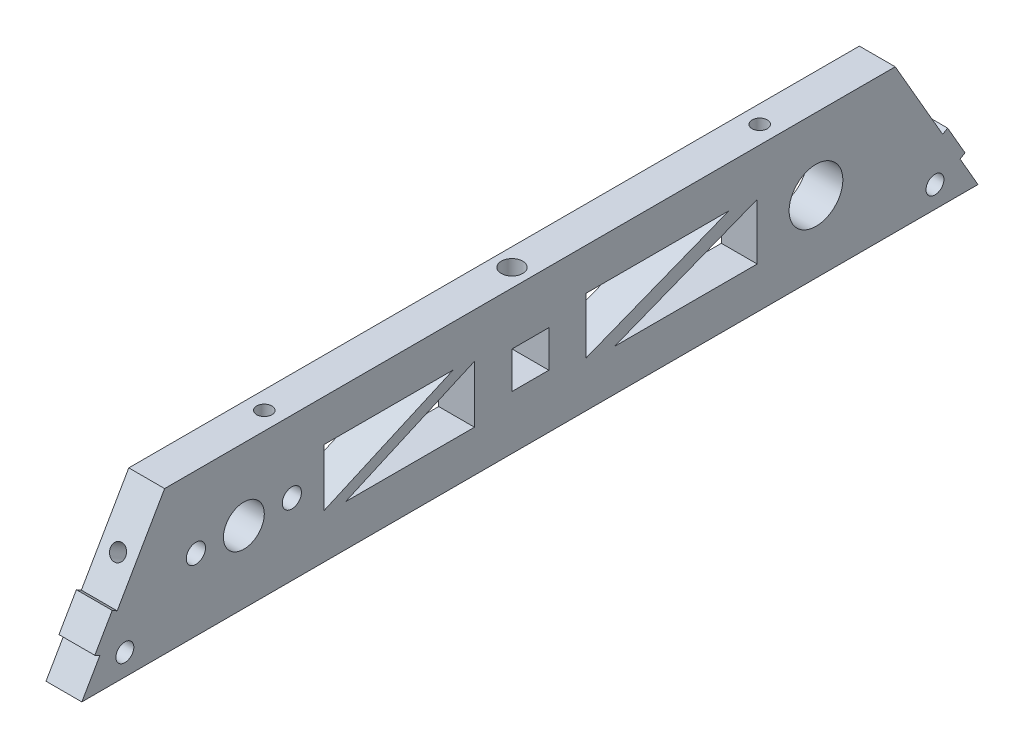
SolidWorks part; units mm, degrees
material "6061-T6 (SS)"
ref_plane "Front Plane" through (0, 0, 0) normal (0, 0, 1) x (1, 0, 0)
ref_plane "Top Plane" through (0, 0, 0) normal (0, 1, 0) x (1, 0, 0)
ref_plane "Right Plane" through (0, 0, 0) normal (1, 0, 0) x (0, 0, -1)
sketch "Sketch1" plane through (0, 0, 0) normal (1, 0, 0) x (0, 0, -1)
  line L0 (0, 0) -> (-14.6647, 25.4)
  line L1 (0, 0) -> (-158.75, 0)
  line L3 (-14.6647, 25.4) -> (-144.0853, 25.4)
  line L4 (-82.55, 9.525) -> (-76.0222, 9.525)
  line L5 (-158.75, 0) -> (-144.0853, 25.4)
  line L6 (-82.55, 9.525) -> (-82.55, 16.0528)
  line L7 (-82.55, 16.0528) -> (-76.0222, 16.0528)
  line L8 (-76.0222, 9.525) -> (-76.0222, 16.0528)
  circle A0 centre (-130.048, 12.7) radius 3.6195
  circle A1 centre (-28.702, 12.7) radius 4.7625
  circle A2 centre (-121.548, 12.7) radius 1.7
  circle A3 centre (-138.548, 12.7) radius 1.7
  dimension "D3" = 7.239
  dimension "D5" = 9.525
  dimension "D9" = 3.4
  dimension "D12" = 3.4
  dimension "D2" = 25.4
  dimension "D4" = 12.7
  dimension "D6" = 158.75
  dimension "D7" = 28.702
  dimension "D8" = 12.7
  dimension "D10" = 8.5
  dimension "D11" = 8.5
  dimension "D13" = 60
  dimension "D14" = 60
  dimension "D15" = 28.702
  dimension "D16" = 6.5278
  dimension "D17" = 6.5278
extrude "Boss-Extrude1" add sketch "Sketch1" along normal blind 6.35
hole_wizard "Tap Drill for #6-32 Tap4" positions "Sketch7" profile "Sketch6" hole size "#6-32" standard "ANSI Inch"
sketch "Sketch7" plane through (0, 25.4, 0) normal (0, 1, 0) x (1, 0, 0)
  line L2 (0, -14.6647) -> (0, -144.0853) construction
  line L4 (6.35, -14.6647) -> (6.35, -144.0853) construction
  line L7 (6.35, -14.6647) -> (0, -14.6647) construction
  line L8 (6.35, -144.0853) -> (0, -144.0853) construction
  point P0 (3.175, -123.2573)
  point P2 (3.175, -35.4927)
  point P16 (3.175, -35.4927)
  point P18 (3.175, -123.2573)
  point P22 (3.175, -123.2573)
  dimension "D1" = 20.828
  dimension "D2" = 20.828
  dimension "D3" = 3.175
  dimension "D4" = 3.175
sketch "Sketch6" plane through (3.175, 25.4, 123.2573) normal (1, 0, 0) x (0, 0, 1)
  line L0 (0, 0) -> (0, 10.9727)
  line L1 (0, 10.9727) -> (1.3525, 10.16)
  line L2 (1.3525, 10.16) -> (1.3525, 0)
  line L5 (1.3525, 0) -> (0, 0)
  line L10 (0, 10.9727) -> (-1.3526, 10.16) construction
  line L11 (0, -6.35) -> (0, 107.95) construction
  dimension "Hole Dia." = 2.7051
  dimension "Hole Depth" = 10.16
  dimension "Drill Angle" = 118
hole_wizard "Tap Drill for #6-32 Tap3" positions "Sketch9" profile "Sketch8" hole size "#6-32" standard "ANSI Inch"
sketch "Sketch9" plane through (0, 0, 0) normal (0, -1, 0) x (-1, 0, 0)
  line L1 (0, -158.75) -> (0, 0) construction
  line L3 (-6.35, 0) -> (0, 0) construction
  line L4 (-6.35, -158.75) -> (0, -158.75) construction
  point P0 (-3.175, -116.84)
  point P2 (-3.175, -35.56)
  dimension "D1" = 35.56
  dimension "D2" = 3.175
  dimension "D3" = 41.91
  dimension "D4" = 3.175
sketch "Sketch8" plane through (3.175, 0, 116.84) normal (1, 0, 0) x (0, 0, -1)
  line L0 (0, 0) -> (0, 10.9727)
  line L1 (0, 10.9727) -> (1.3525, 10.16)
  line L2 (1.3525, 10.16) -> (1.3525, 0)
  line L5 (1.3525, 0) -> (0, 0)
  line L10 (0, 10.9727) -> (-1.3526, 10.16) construction
  line L11 (0, -6.35) -> (0, 107.95) construction
  dimension "Hole Dia." = 2.7051
  dimension "Hole Depth" = 10.16
  dimension "Drill Angle" = 118
sketch "Sketch11" plane through (0, 68.7408, 119.0625) normal (0, 0.5, 0.866) x (1, 0, 0)
  line L0 (0, -50.0456) -> (0, -79.375) construction
  line L1 (0, -66.8528) -> (6.35, -66.8528)
  line L2 (0, -66.8528) -> (0, -73.025)
  line L3 (0, -73.025) -> (6.35, -73.025)
  line L4 (6.35, -66.8528) -> (6.35, -73.025)
  line L5 (6.35, -50.0456) -> (6.35, -79.375) construction
  line L6 (6.35, -79.375) -> (0, -79.375) construction
  dimension "D1" = 6.1722
  dimension "D2" = 6.35
extrude "Boss-Extrude2" add sketch "Sketch11" along normal blind 1.016
sketch "Sketch12" plane through (0, 0, 0) normal (0, 0.5, -0.866) x (-1, 0, 0)
  line L0 (-6.35, 0) -> (-6.35, 29.3294) construction
  line L1 (-6.35, 12.5222) -> (0, 12.5222)
  line L2 (-6.35, 12.5222) -> (-6.35, 6.35)
  line L3 (-6.35, 6.35) -> (0, 6.35)
  line L4 (0, 12.5222) -> (0, 6.35)
  line L5 (0, 0) -> (0, 29.3294) construction
  line L6 (-6.35, 0) -> (0, 0) construction
  dimension "D1" = 6.1722
  dimension "D2" = 6.35
extrude "Boss-Extrude3" add sketch "Sketch12" along normal blind 1.016
hole_wizard "Tap Drill for #6-32 Tap1" positions "Sketch14" profile "Sketch13" hole size "#6-32" standard "ANSI Inch"
sketch "Sketch14" plane through (0, 68.7408, 119.0625) normal (0, 0.5, 0.866) x (1, 0, 0)
  line L0 (6.35, -50.0456) -> (6.35, -66.8528) construction
  line L1 (6.35, -50.0456) -> (0, -50.0456) construction
  point P0 (3.175, -60.2056)
  dimension "D1" = 3.175
  dimension "D2" = 10.16
sketch "Sketch13" plane through (3.175, 16.6012, 149.1653) normal (1, 0, 0) x (0, -0.866, 0.5)
  line L0 (0, 0) -> (0, 8.4327)
  line L1 (0, 8.4327) -> (1.3525, 7.62)
  line L2 (1.3525, 7.62) -> (1.3525, 0)
  line L5 (1.3525, 0) -> (0, 0)
  line L10 (0, 8.4327) -> (-1.3526, 7.62) construction
  line L11 (0, -6.35) -> (0, 107.95) construction
  dimension "Hole Dia." = 2.7051
  dimension "Hole Depth" = 7.62
  dimension "Drill Angle" = 118
hole_wizard "Tap Drill for #6-32 Tap2" positions "Sketch16" profile "Sketch15" hole size "#6-32" standard "ANSI Inch"
sketch "Sketch16" plane through (0, 0, 0) normal (0, 0.5, -0.866) x (-1, 0, 0)
  line L0 (0, 12.5222) -> (0, 29.3294) construction
  line L1 (-6.35, 29.3294) -> (0, 29.3294) construction
  point P0 (-3.175, 19.1694)
  dimension "D1" = 3.175
  dimension "D2" = 10.16
sketch "Sketch15" plane through (3.175, 16.6012, 9.5847) normal (1, 0, 0) x (0, 0.866, 0.5)
  line L0 (0, 0) -> (0, 8.4327)
  line L1 (0, 8.4327) -> (1.3525, 7.62)
  line L2 (1.3525, 7.62) -> (1.3525, 0)
  line L5 (1.3525, 0) -> (0, 0)
  line L10 (0, 8.4327) -> (-1.3525, 7.62) construction
  line L11 (0, -6.35) -> (0, 107.95) construction
  dimension "Hole Dia." = 2.7051
  dimension "Hole Depth" = 7.62
  dimension "Drill Angle" = 118
hole_wizard "#6 Clearance Hole1" positions "Sketch18" profile "Sketch17" hole size "#6" standard "ANSI Inch"
sketch "Sketch18" plane through (0, 25.4, 0) normal (0, 1, 0) x (1, 0, 0)
  line L0 (0, -14.6647) -> (0, -144.0853) construction
  line L1 (6.35, -158.75) -> (0, -158.75) construction
  point P0 (3.175, -79.375)
  dimension "D1" = 3.175
  dimension "D2" = 79.375
sketch "Sketch17" plane through (3.175, 25.4, 79.375) normal (1, 0, 0) x (0, 0, 1)
  line L0 (0, 0) -> (0, 13.8408)
  line L1 (0, 13.8408) -> (1.8986, 12.7)
  line L2 (1.8986, 12.7) -> (1.8986, 0)
  line L5 (1.8986, 0) -> (0, 0)
  line L10 (0, 13.8408) -> (-1.8987, 12.7) construction
  line L11 (0, -6.35) -> (0, 107.95) construction
  dimension "Hole Dia." = 3.7973
  dimension "Hole Depth" = 12.7
  dimension "Drill Angle" = 118
sketch "Sketch19" plane through (0, 0, 0) normal (-1, 0, 0) x (0, 0, 1)
  circle A0 centre (151.13, 3.81) radius 1.5875
  circle A1 centre (7.62, 3.81) radius 1.5875
  dimension "D1" = 3.175
extrude "Cut-Extrude1" cut sketch "Sketch19" against normal through all
sketch "Sketch20" plane through (0, 0, 0) normal (-1, 0, 0) x (0, 0, 1)
  line L0 (14.6647, 25.4) -> (144.0853, 25.4) construction
  line L1 (38.1, 19.05) -> (70.4342, 19.05)
  line L2 (38.1, 19.05) -> (38.1, 6.35)
  line L3 (38.1, 6.35) -> (70.4342, 6.35)
  line L4 (70.4342, 19.05) -> (70.4342, 6.35)
  line L5 (158.75, 0) -> (0, 0) construction
  line L6 (76.0222, 9.525) -> (76.0222, 16.0528) construction
  line L7 (116.84, 19.05) -> (88.1794, 19.05)
  line L8 (116.84, 19.05) -> (116.84, 6.35)
  line L9 (116.84, 6.35) -> (88.1794, 6.35)
  line L10 (88.1794, 19.05) -> (88.1794, 6.35)
  line L11 (38.1, 19.05) -> (70.4342, 6.35)
  line L12 (70.4342, 6.35) -> (70.4414, 6.0431)
  line L13 (88.1794, 19.05) -> (116.84, 6.35)
  line L14 (37.6357, 17.8679) -> (69.9699, 5.1679)
  line L15 (38.5643, 20.2321) -> (70.8985, 7.5321)
  line L16 (37.084, 19.05) -> (37.084, 5.334)
  line L17 (37.084, 5.334) -> (70.4342, 5.334)
  line L18 (38.1, 18.034) -> (69.4182, 18.034)
  line L19 (69.4182, 18.034) -> (69.4182, 6.35)
  line L20 (117.856, 20.066) -> (117.856, 6.35)
  line L21 (117.856, 20.066) -> (88.1794, 20.066)
  line L22 (87.1634, 19.05) -> (87.1634, 5.334)
  line L23 (116.84, 5.334) -> (87.1634, 5.334)
  line L24 (87.7678, 18.1211) -> (116.4284, 5.4211)
  line L25 (39.116, 19.05) -> (39.116, 7.366)
  line L26 (39.116, 7.366) -> (70.4342, 7.366)
  line L27 (38.1, 20.066) -> (71.4502, 20.066)
  line L28 (71.4502, 20.066) -> (71.4502, 6.35)
  line L29 (115.824, 18.034) -> (115.824, 6.35)
  line L30 (115.824, 18.034) -> (88.1794, 18.034)
  line L31 (89.1954, 19.05) -> (89.1954, 7.366)
  line L32 (116.84, 7.366) -> (89.1954, 7.366)
  line L33 (88.591, 19.9789) -> (117.2516, 7.2789)
  dimension "D1" = 6.35
  dimension "D2" = 6.35
  dimension "D3" = 38.1
  dimension "D4" = 5.588
  dimension "D5" = 28.6606
  dimension "D6" = 6.35
  dimension "D7" = 41.91
  dimension "D8" = 1.27
  dimension "D9" = 1.27
  dimension "D10" = 1.016
  dimension "D11" = 1.016
extrude "Cut-Extrude2" cut sketch "Sketch20" against normal through all contours L25 L26 L14 | L19 L18 L15 | L32 L24 L31 | L30 L33 L29
sketch "Sketch21" plane through (0, 0, 0) normal (-1, 0, 0) x (0, 0, 1)
  line L0 (14.6647, 25.4) -> (144.0853, 25.4) construction
  line L1 (21.7996, 20.6375) -> (20.4248, 23.0187)
  line L2 (20.4248, 23.0187) -> (17.6752, 23.0187)
  line L3 (17.6752, 23.0187) -> (16.3004, 20.6375)
  line L4 (16.3004, 20.6375) -> (17.6752, 18.2563)
  line L5 (17.6752, 18.2563) -> (20.4248, 18.2563)
  line L6 (20.4248, 18.2563) -> (21.7996, 20.6375)
  line L7 (0, -3.4925) -> (0, 3.4925) construction
  line L8 (28.1496, 20.6375) -> (26.7748, 23.0187)
  line L9 (26.7748, 23.0187) -> (24.0252, 23.0187)
  line L10 (24.0252, 23.0187) -> (22.6504, 20.6375)
  line L11 (22.6504, 20.6375) -> (24.0252, 18.2563)
  line L12 (24.0252, 18.2563) -> (26.7748, 18.2563)
  line L13 (26.7748, 18.2563) -> (28.1496, 20.6375)
  line L14 (34.4996, 20.6375) -> (33.1248, 23.0187) [skipped]
  line L15 (33.1248, 23.0187) -> (30.3752, 23.0187) [skipped]
  line L16 (30.3752, 23.0187) -> (29.0004, 20.6375) [skipped]
  line L17 (29.0004, 20.6375) -> (30.3752, 18.2563) [skipped]
  line L18 (30.3752, 18.2563) -> (33.1248, 18.2563) [skipped]
  line L19 (33.1248, 18.2563) -> (34.4996, 20.6375) [skipped]
  line L20 (40.8496, 20.6375) -> (39.4748, 23.0187) [skipped]
  line L21 (39.4748, 23.0187) -> (36.7252, 23.0187) [skipped]
  line L22 (36.7252, 23.0187) -> (35.3504, 20.6375) [skipped]
  line L23 (35.3504, 20.6375) -> (36.7252, 18.2563) [skipped]
  line L24 (36.7252, 18.2563) -> (39.4748, 18.2563) [skipped]
  line L25 (39.4748, 18.2563) -> (40.8496, 20.6375) [skipped]
  line L26 (47.1996, 20.6375) -> (45.8248, 23.0187)
  line L27 (45.8248, 23.0187) -> (43.0752, 23.0187)
  line L28 (43.0752, 23.0187) -> (41.7004, 20.6375)
  line L29 (41.7004, 20.6375) -> (43.0752, 18.2563)
  line L30 (43.0752, 18.2563) -> (45.8248, 18.2563)
  line L31 (45.8248, 18.2563) -> (47.1996, 20.6375)
  line L32 (53.5496, 20.6375) -> (52.1748, 23.0187)
  line L33 (52.1748, 23.0187) -> (49.4252, 23.0187)
  line L34 (49.4252, 23.0187) -> (48.0504, 20.6375)
  line L35 (48.0504, 20.6375) -> (49.4252, 18.2563)
  line L36 (49.4252, 18.2563) -> (52.1748, 18.2563)
  line L37 (52.1748, 18.2563) -> (53.5496, 20.6375)
  line L38 (59.8996, 20.6375) -> (58.5248, 23.0187)
  line L39 (58.5248, 23.0187) -> (55.7752, 23.0187)
  line L40 (55.7752, 23.0187) -> (54.4004, 20.6375)
  line L41 (54.4004, 20.6375) -> (55.7752, 18.2563)
  line L42 (55.7752, 18.2563) -> (58.5248, 18.2563)
  line L43 (58.5248, 18.2563) -> (59.8996, 20.6375)
  line L44 (66.2496, 20.6375) -> (64.8748, 23.0187)
  line L45 (64.8748, 23.0187) -> (62.1252, 23.0187)
  line L46 (62.1252, 23.0187) -> (60.7504, 20.6375)
  line L47 (60.7504, 20.6375) -> (62.1252, 18.2563)
  line L48 (62.1252, 18.2563) -> (64.8748, 18.2563)
  line L49 (64.8748, 18.2563) -> (66.2496, 20.6375)
  line L50 (72.5996, 20.6375) -> (71.2248, 23.0187)
  line L51 (71.2248, 23.0187) -> (68.4752, 23.0187)
  line L52 (68.4752, 23.0187) -> (67.1004, 20.6375)
  line L53 (67.1004, 20.6375) -> (68.4752, 18.2563)
  line L54 (68.4752, 18.2563) -> (71.2248, 18.2563)
  line L55 (71.2248, 18.2563) -> (72.5996, 20.6375)
  line L56 (78.9496, 20.6375) -> (77.5748, 23.0187) [skipped]
  line L57 (77.5748, 23.0187) -> (74.8252, 23.0187) [skipped]
  line L58 (74.8252, 23.0187) -> (73.4504, 20.6375) [skipped]
  line L59 (73.4504, 20.6375) -> (74.8252, 18.2563) [skipped]
  line L60 (74.8252, 18.2563) -> (77.5748, 18.2563) [skipped]
  line L61 (77.5748, 18.2563) -> (78.9496, 20.6375) [skipped]
  line L62 (85.2996, 20.6375) -> (83.9248, 23.0187) [skipped]
  line L63 (83.9248, 23.0187) -> (81.1752, 23.0187) [skipped]
  line L64 (81.1752, 23.0187) -> (79.8004, 20.6375) [skipped]
  line L65 (79.8004, 20.6375) -> (81.1752, 18.2563) [skipped]
  line L66 (81.1752, 18.2563) -> (83.9248, 18.2563) [skipped]
  line L67 (83.9248, 18.2563) -> (85.2996, 20.6375) [skipped]
  line L68 (91.6496, 20.6375) -> (90.2748, 23.0187)
  line L69 (90.2748, 23.0187) -> (87.5252, 23.0187)
  line L70 (87.5252, 23.0187) -> (86.1504, 20.6375)
  line L71 (86.1504, 20.6375) -> (87.5252, 18.2563)
  line L72 (87.5252, 18.2563) -> (90.2748, 18.2563)
  line L73 (90.2748, 18.2563) -> (91.6496, 20.6375)
  line L74 (97.9996, 20.6375) -> (96.6248, 23.0187)
  line L75 (96.6248, 23.0187) -> (93.8752, 23.0187)
  line L76 (93.8752, 23.0187) -> (92.5004, 20.6375)
  line L77 (92.5004, 20.6375) -> (93.8752, 18.2563)
  line L78 (93.8752, 18.2563) -> (96.6248, 18.2563)
  line L79 (96.6248, 18.2563) -> (97.9996, 20.6375)
  line L80 (104.3496, 20.6375) -> (102.9748, 23.0187)
  line L81 (102.9748, 23.0187) -> (100.2252, 23.0187)
  line L82 (100.2252, 23.0187) -> (98.8504, 20.6375)
  line L83 (98.8504, 20.6375) -> (100.2252, 18.2563)
  line L84 (100.2252, 18.2563) -> (102.9748, 18.2563)
  line L85 (102.9748, 18.2563) -> (104.3496, 20.6375)
  line L86 (110.6996, 20.6375) -> (109.3248, 23.0187)
  line L87 (109.3248, 23.0187) -> (106.5752, 23.0187)
  line L88 (106.5752, 23.0187) -> (105.2004, 20.6375)
  line L89 (105.2004, 20.6375) -> (106.5752, 18.2563)
  line L90 (106.5752, 18.2563) -> (109.3248, 18.2563)
  line L91 (109.3248, 18.2563) -> (110.6996, 20.6375)
  line L92 (117.0496, 20.6375) -> (115.6748, 23.0187)
  line L93 (115.6748, 23.0187) -> (112.9252, 23.0187)
  line L94 (112.9252, 23.0187) -> (111.5504, 20.6375)
  line L95 (111.5504, 20.6375) -> (112.9252, 18.2563)
  line L96 (112.9252, 18.2563) -> (115.6748, 18.2563)
  line L97 (115.6748, 18.2563) -> (117.0496, 20.6375)
  line L98 (123.3996, 20.6375) -> (122.0248, 23.0187) [skipped]
  line L99 (122.0248, 23.0187) -> (119.2752, 23.0187) [skipped]
  line L100 (119.2752, 23.0187) -> (117.9004, 20.6375) [skipped]
  line L101 (117.9004, 20.6375) -> (119.2752, 18.2563) [skipped]
  line L102 (119.2752, 18.2563) -> (122.0248, 18.2563) [skipped]
  line L103 (122.0248, 18.2563) -> (123.3996, 20.6375) [skipped]
  line L104 (129.7496, 20.6375) -> (128.3748, 23.0187) [skipped]
  line L105 (128.3748, 23.0187) -> (125.6252, 23.0187) [skipped]
  line L106 (125.6252, 23.0187) -> (124.2504, 20.6375) [skipped]
  line L107 (124.2504, 20.6375) -> (125.6252, 18.2563) [skipped]
  line L108 (125.6252, 18.2563) -> (128.3748, 18.2563) [skipped]
  line L109 (128.3748, 18.2563) -> (129.7496, 20.6375) [skipped]
  line L110 (136.0996, 20.6375) -> (134.7248, 23.0187)
  line L111 (134.7248, 23.0187) -> (131.9752, 23.0187)
  line L112 (131.9752, 23.0187) -> (130.6004, 20.6375)
  line L113 (130.6004, 20.6375) -> (131.9752, 18.2563)
  line L114 (131.9752, 18.2563) -> (134.7248, 18.2563)
  line L115 (134.7248, 18.2563) -> (136.0996, 20.6375)
  line L116 (142.4496, 20.6375) -> (141.0748, 23.0187)
  line L117 (141.0748, 23.0187) -> (138.3252, 23.0187)
  line L118 (138.3252, 23.0187) -> (136.9504, 20.6375)
  line L119 (136.9504, 20.6375) -> (138.3252, 18.2563)
  line L120 (138.3252, 18.2563) -> (141.0748, 18.2563)
  line L121 (141.0748, 18.2563) -> (142.4496, 20.6375)
  line L122 (148.7996, 4.8895) -> (147.4248, 7.2707)
  line L123 (147.4248, 7.2707) -> (144.6752, 7.2707)
  line L124 (144.6752, 7.2707) -> (143.3004, 4.8895)
  line L125 (143.3004, 4.8895) -> (144.6752, 2.5083)
  line L126 (144.6752, 2.5083) -> (147.4248, 2.5083)
  line L127 (147.4248, 2.5083) -> (148.7996, 4.8895)
  line L128 (40.8496, 12.7635) -> (39.4748, 15.1447)
  line L129 (39.4748, 15.1447) -> (36.7252, 15.1447)
  line L130 (36.7252, 15.1447) -> (35.3504, 12.7635)
  line L131 (35.3504, 12.7635) -> (36.7252, 10.3822)
  line L132 (36.7252, 10.3822) -> (39.4748, 10.3822)
  line L133 (39.4748, 10.3822) -> (40.8496, 12.7635)
  line L134 (47.1996, 12.7635) -> (45.8248, 15.1447)
  line L135 (45.8248, 15.1447) -> (43.0752, 15.1447)
  line L136 (43.0752, 15.1447) -> (41.7004, 12.7635)
  line L137 (41.7004, 12.7635) -> (43.0752, 10.3823)
  line L138 (43.0752, 10.3823) -> (45.8248, 10.3823)
  line L139 (45.8248, 10.3823) -> (47.1996, 12.7635)
  line L140 (53.5496, 12.7635) -> (52.1748, 15.1447)
  line L141 (52.1748, 15.1447) -> (49.4252, 15.1447)
  line L142 (49.4252, 15.1447) -> (48.0504, 12.7635)
  line L143 (48.0504, 12.7635) -> (49.4252, 10.3823)
  line L144 (49.4252, 10.3823) -> (52.1748, 10.3823)
  line L145 (52.1748, 10.3823) -> (53.5496, 12.7635)
  line L146 (59.8996, 12.7635) -> (58.5248, 15.1447)
  line L147 (58.5248, 15.1447) -> (55.7752, 15.1447)
  line L148 (55.7752, 15.1447) -> (54.4004, 12.7635)
  line L149 (54.4004, 12.7635) -> (55.7752, 10.3823)
  line L150 (55.7752, 10.3823) -> (58.5248, 10.3823)
  line L151 (58.5248, 10.3823) -> (59.8996, 12.7635)
  line L152 (66.2496, 12.7635) -> (64.8748, 15.1447)
  line L153 (64.8748, 15.1447) -> (62.1252, 15.1447)
  line L154 (62.1252, 15.1447) -> (60.7504, 12.7635)
  line L155 (60.7504, 12.7635) -> (62.1252, 10.3823)
  line L156 (62.1252, 10.3823) -> (64.8748, 10.3823)
  line L157 (64.8748, 10.3823) -> (66.2496, 12.7635)
  line L158 (72.5996, 12.7635) -> (71.2248, 15.1447)
  line L159 (71.2248, 15.1447) -> (68.4752, 15.1447)
  line L160 (68.4752, 15.1447) -> (67.1004, 12.7635)
  line L161 (67.1004, 12.7635) -> (68.4752, 10.3823)
  line L162 (68.4752, 10.3823) -> (71.2248, 10.3823)
  line L163 (71.2248, 10.3823) -> (72.5996, 12.7635)
  line L164 (91.6496, 12.7635) -> (90.2748, 15.1447)
  line L165 (90.2748, 15.1447) -> (87.5252, 15.1447)
  line L166 (87.5252, 15.1447) -> (86.1504, 12.7635)
  line L167 (86.1504, 12.7635) -> (87.5252, 10.3823)
  line L168 (87.5252, 10.3823) -> (90.2748, 10.3823)
  line L169 (90.2748, 10.3823) -> (91.6496, 12.7635)
  line L170 (97.9996, 12.7635) -> (96.6248, 15.1447)
  line L171 (96.6248, 15.1447) -> (93.8752, 15.1447)
  line L172 (93.8752, 15.1447) -> (92.5004, 12.7635)
  line L173 (92.5004, 12.7635) -> (93.8752, 10.3823)
  line L174 (93.8752, 10.3823) -> (96.6248, 10.3823)
  line L175 (96.6248, 10.3823) -> (97.9996, 12.7635)
  line L176 (104.3496, 12.7635) -> (102.9748, 15.1447)
  line L177 (102.9748, 15.1447) -> (100.2252, 15.1447)
  line L178 (100.2252, 15.1447) -> (98.8504, 12.7635)
  line L179 (98.8504, 12.7635) -> (100.2252, 10.3823)
  line L180 (100.2252, 10.3823) -> (102.9748, 10.3823)
  line L181 (102.9748, 10.3823) -> (104.3496, 12.7635)
  line L182 (110.6996, 12.7635) -> (109.3248, 15.1447)
  line L183 (109.3248, 15.1447) -> (106.5752, 15.1447)
  line L184 (106.5752, 15.1447) -> (105.2004, 12.7635)
  line L185 (105.2004, 12.7635) -> (106.5752, 10.3823)
  line L186 (106.5752, 10.3823) -> (109.3248, 10.3823)
  line L187 (109.3248, 10.3823) -> (110.6996, 12.7635)
  line L188 (117.0496, 12.7635) -> (115.6748, 15.1447)
  line L189 (115.6748, 15.1447) -> (112.9252, 15.1447)
  line L190 (112.9252, 15.1447) -> (111.5504, 12.7635)
  line L191 (111.5504, 12.7635) -> (112.9252, 10.3823)
  line L192 (112.9252, 10.3823) -> (115.6748, 10.3823)
  line L193 (115.6748, 10.3823) -> (117.0496, 12.7635)
  line L194 (129.7496, 4.8895) -> (128.3748, 7.2707)
  line L195 (128.3748, 7.2707) -> (125.6252, 7.2707)
  line L196 (125.6252, 7.2707) -> (124.2504, 4.8895)
  line L197 (124.2504, 4.8895) -> (125.6252, 2.5082)
  line L198 (125.6252, 2.5082) -> (128.3748, 2.5082)
  line L199 (128.3748, 2.5082) -> (129.7496, 4.8895)
  line L206 (21.7996, 4.8895) -> (20.4248, 7.2707)
  line L207 (20.4248, 7.2707) -> (17.6752, 7.2707)
  line L208 (17.6752, 7.2707) -> (16.3004, 4.8895)
  line L209 (16.3004, 4.8895) -> (17.6752, 2.5083)
  line L210 (17.6752, 2.5083) -> (20.4248, 2.5083)
  line L211 (20.4248, 2.5083) -> (21.7996, 4.8895)
  line L212 (28.1496, 4.8895) -> (26.7748, 7.2707)
  line L213 (26.7748, 7.2707) -> (24.0252, 7.2707)
  line L214 (24.0252, 7.2707) -> (22.6504, 4.8895)
  line L215 (22.6504, 4.8895) -> (24.0252, 2.5083)
  line L216 (24.0252, 2.5083) -> (26.7748, 2.5083)
  line L217 (26.7748, 2.5083) -> (28.1496, 4.8895)
  line L218 (47.1996, 4.8895) -> (45.8248, 7.2707)
  line L219 (45.8248, 7.2707) -> (43.0752, 7.2707)
  line L220 (43.0752, 7.2707) -> (41.7004, 4.8895)
  line L221 (41.7004, 4.8895) -> (43.0752, 2.5083)
  line L222 (43.0752, 2.5083) -> (45.8248, 2.5083)
  line L223 (45.8248, 2.5083) -> (47.1996, 4.8895)
  line L224 (53.5496, 4.8895) -> (52.1748, 7.2707)
  line L225 (52.1748, 7.2707) -> (49.4252, 7.2707)
  line L226 (49.4252, 7.2707) -> (48.0504, 4.8895)
  line L227 (48.0504, 4.8895) -> (49.4252, 2.5083)
  line L228 (49.4252, 2.5083) -> (52.1748, 2.5083)
  line L229 (52.1748, 2.5083) -> (53.5496, 4.8895)
  line L230 (59.8996, 4.8895) -> (58.5248, 7.2707)
  line L231 (58.5248, 7.2707) -> (55.7752, 7.2707)
  line L232 (55.7752, 7.2707) -> (54.4004, 4.8895)
  line L233 (54.4004, 4.8895) -> (55.7752, 2.5083)
  line L234 (55.7752, 2.5083) -> (58.5248, 2.5083)
  line L235 (58.5248, 2.5083) -> (59.8996, 4.8895)
  line L236 (66.2496, 4.8895) -> (64.8748, 7.2707)
  line L237 (64.8748, 7.2707) -> (62.1252, 7.2707)
  line L238 (62.1252, 7.2707) -> (60.7504, 4.8895)
  line L239 (60.7504, 4.8895) -> (62.1252, 2.5083)
  line L240 (62.1252, 2.5083) -> (64.8748, 2.5083)
  line L241 (64.8748, 2.5083) -> (66.2496, 4.8895)
  line L242 (72.5996, 4.8895) -> (71.2248, 7.2707)
  line L243 (71.2248, 7.2707) -> (68.4752, 7.2707)
  line L244 (68.4752, 7.2707) -> (67.1004, 4.8895)
  line L245 (67.1004, 4.8895) -> (68.4752, 2.5083)
  line L246 (68.4752, 2.5083) -> (71.2248, 2.5083)
  line L247 (71.2248, 2.5083) -> (72.5996, 4.8895)
  line L248 (91.6496, 4.8895) -> (90.2748, 7.2707)
  line L249 (90.2748, 7.2707) -> (87.5252, 7.2707)
  line L250 (87.5252, 7.2707) -> (86.1504, 4.8895)
  line L251 (86.1504, 4.8895) -> (87.5252, 2.5083)
  line L252 (87.5252, 2.5083) -> (90.2748, 2.5083)
  line L253 (90.2748, 2.5083) -> (91.6496, 4.8895)
  line L254 (97.9996, 4.8895) -> (96.6248, 7.2707)
  line L255 (96.6248, 7.2707) -> (93.8752, 7.2707)
  line L256 (93.8752, 7.2707) -> (92.5004, 4.8895)
  line L257 (92.5004, 4.8895) -> (93.8752, 2.5083)
  line L258 (93.8752, 2.5083) -> (96.6248, 2.5083)
  line L259 (96.6248, 2.5083) -> (97.9996, 4.8895)
  line L260 (104.3496, 4.8895) -> (102.9748, 7.2707)
  line L261 (102.9748, 7.2707) -> (100.2252, 7.2707)
  line L262 (100.2252, 7.2707) -> (98.8504, 4.8895)
  line L263 (98.8504, 4.8895) -> (100.2252, 2.5083)
  line L264 (100.2252, 2.5083) -> (102.9748, 2.5083)
  line L265 (102.9748, 2.5083) -> (104.3496, 4.8895)
  line L266 (110.6996, 4.8895) -> (109.3248, 7.2707)
  line L267 (109.3248, 7.2707) -> (106.5752, 7.2707)
  line L268 (106.5752, 7.2707) -> (105.2004, 4.8895)
  line L269 (105.2004, 4.8895) -> (106.5752, 2.5083)
  line L270 (106.5752, 2.5083) -> (109.3248, 2.5083)
  line L271 (109.3248, 2.5083) -> (110.6996, 4.8895)
  line L278 (136.0996, 4.8895) -> (134.7248, 7.2707)
  line L279 (134.7248, 7.2707) -> (131.9752, 7.2707)
  line L280 (131.9752, 7.2707) -> (130.6004, 4.8895)
  line L281 (130.6004, 4.8895) -> (131.9752, 2.5083)
  line L282 (131.9752, 2.5083) -> (134.7248, 2.5083)
  line L283 (134.7248, 2.5083) -> (136.0996, 4.8895)
  line L284 (142.4496, 4.8895) -> (141.0748, 7.2707)
  line L285 (141.0748, 7.2707) -> (138.3252, 7.2707)
  line L286 (138.3252, 7.2707) -> (136.9504, 4.8895)
  line L287 (136.9504, 4.8895) -> (138.3252, 2.5083)
  line L288 (138.3252, 2.5083) -> (141.0748, 2.5083)
  line L289 (141.0748, 2.5083) -> (142.4496, 4.8895)
  line L290 (78.9496, 4.8895) -> (77.5748, 7.2707)
  line L291 (77.5748, 7.2707) -> (74.8252, 7.2707)
  line L292 (74.8252, 7.2707) -> (73.4504, 4.8895)
  line L293 (73.4504, 4.8895) -> (74.8252, 2.5083)
  line L294 (74.8252, 2.5083) -> (77.5748, 2.5083)
  line L295 (77.5748, 2.5083) -> (78.9496, 4.8895)
  line L296 (85.2996, 4.8895) -> (83.9248, 7.2707)
  line L297 (83.9248, 7.2707) -> (81.1752, 7.2707)
  line L298 (81.1752, 7.2707) -> (79.8004, 4.8895)
  line L299 (79.8004, 4.8895) -> (81.1752, 2.5083)
  line L300 (81.1752, 2.5083) -> (83.9248, 2.5083)
  line L301 (83.9248, 2.5083) -> (85.2996, 4.8895)
  line L302 (28.1496, 12.7635) -> (26.7748, 15.1447) [skipped]
  line L303 (26.7748, 15.1447) -> (24.0252, 15.1447) [skipped]
  line L304 (24.0252, 15.1447) -> (22.6504, 12.7635) [skipped]
  line L305 (22.6504, 12.7635) -> (24.0252, 10.3823) [skipped]
  line L306 (24.0252, 10.3823) -> (26.7748, 10.3823) [skipped]
  line L307 (26.7748, 10.3823) -> (28.1496, 12.7635) [skipped]
  line L308 (15.4496, 4.8895) -> (14.0748, 7.2707)
  line L309 (14.0748, 7.2707) -> (11.3252, 7.2707)
  line L310 (11.3252, 7.2707) -> (9.9504, 4.8895)
  line L311 (9.9504, 4.8895) -> (11.3252, 2.5082)
  line L312 (11.3252, 2.5082) -> (14.0748, 2.5082)
  line L313 (14.0748, 2.5082) -> (15.4496, 4.8895)
  line L314 (136.0996, 12.7635) -> (134.7248, 15.1447) [skipped]
  line L315 (134.7248, 15.1447) -> (131.9752, 15.1447) [skipped]
  line L316 (131.9752, 15.1447) -> (130.6004, 12.7635) [skipped]
  line L317 (130.6004, 12.7635) -> (131.9752, 10.3823) [skipped]
  line L318 (134.7248, 10.3823) -> (136.0996, 12.7635) [skipped]
  line L319 (142.4496, 12.7635) -> (141.0748, 15.1447) [skipped]
  line L320 (141.0748, 15.1447) -> (138.3252, 15.1447) [skipped]
  line L321 (138.3252, 15.1447) -> (136.9504, 12.7635) [skipped]
  line L322 (136.9504, 12.7635) -> (138.3252, 10.3823) [skipped]
  line L323 (141.0748, 10.3823) -> (142.4496, 12.7635) [skipped]
  line L324 (131.9752, 10.3823) -> (134.7248, 10.3823) [skipped]
  line L325 (138.3252, 10.3823) -> (141.0748, 10.3823) [skipped]
  line L326 (21.7996, 12.7635) -> (20.4248, 15.1447) [skipped]
  line L327 (20.4248, 15.1447) -> (17.6752, 15.1447) [skipped]
  line L328 (17.6752, 15.1447) -> (16.3004, 12.7635) [skipped]
  line L329 (16.3004, 12.7635) -> (17.6752, 10.3823) [skipped]
  line L330 (17.6752, 10.3823) -> (20.4248, 10.3823) [skipped]
  line L331 (20.4248, 10.3823) -> (21.7996, 12.7635) [skipped]
  line L338 (117.0496, 4.8895) -> (115.6748, 7.2707) [skipped]
  line L339 (115.6748, 7.2707) -> (112.9252, 7.2707) [skipped]
  line L340 (112.9252, 7.2707) -> (111.5504, 4.8895) [skipped]
  line L341 (111.5504, 4.8895) -> (112.9252, 2.5083) [skipped]
  line L342 (112.9252, 2.5083) -> (115.6748, 2.5083) [skipped]
  line L343 (115.6748, 2.5083) -> (117.0496, 4.8895) [skipped]
  line L344 (122.0248, 7.2707) -> (119.2752, 7.2707) [skipped]
  line L345 (119.2752, 7.2707) -> (117.9004, 4.8895) [skipped]
  line L346 (117.9004, 4.8895) -> (119.2752, 2.5082) [skipped]
  line L347 (119.2752, 2.5082) -> (122.0248, 2.5082) [skipped]
  line L348 (122.0248, 2.5082) -> (123.3996, 4.8895) [skipped]
  line L349 (123.3996, 4.8895) -> (122.0248, 7.2707) [skipped]
  circle A0 centre (19.05, 20.6375) radius 2.3813 construction
  circle A1 centre (25.4, 20.6375) radius 2.3813 construction
  circle A2 centre (31.75, 20.6375) radius 2.3812 construction
  circle A3 centre (38.1, 20.6375) radius 2.3812 construction
  circle A4 centre (44.45, 20.6375) radius 2.3812 construction
  circle A5 centre (50.8, 20.6375) radius 2.3812 construction
  circle A6 centre (57.15, 20.6375) radius 2.3812 construction
  circle A7 centre (63.5, 20.6375) radius 2.3813 construction
  circle A8 centre (69.85, 20.6375) radius 2.3813 construction
  circle A9 centre (76.2, 20.6375) radius 2.3813 construction
  circle A10 centre (82.55, 20.6375) radius 2.3813 construction
  circle A11 centre (88.9, 20.6375) radius 2.3813 construction
  circle A12 centre (95.25, 20.6375) radius 2.3813 construction
  circle A13 centre (101.6, 20.6375) radius 2.3813 construction
  circle A14 centre (107.95, 20.6375) radius 2.3813 construction
  circle A15 centre (114.3, 20.6375) radius 2.3813 construction
  circle A16 centre (120.65, 20.6375) radius 2.3813 construction
  circle A17 centre (127, 20.6375) radius 2.3813 construction
  circle A18 centre (133.35, 20.6375) radius 2.3813 construction
  circle A19 centre (139.7, 20.6375) radius 2.3813 construction
  circle A20 centre (146.05, 4.8895) radius 2.3813 construction
  circle A21 centre (38.1, 12.7635) radius 2.3812 construction
  circle A22 centre (44.45, 12.7635) radius 2.3812 construction
  circle A23 centre (50.8, 12.7635) radius 2.3812 construction
  circle A24 centre (57.15, 12.7635) radius 2.3812 construction
  circle A25 centre (63.5, 12.7635) radius 2.3813 construction
  circle A26 centre (69.85, 12.7635) radius 2.3813 construction
  circle A27 centre (88.9, 12.7635) radius 2.3813 construction
  circle A28 centre (95.25, 12.7635) radius 2.3813 construction
  circle A29 centre (101.6, 12.7635) radius 2.3813 construction
  circle A30 centre (107.95, 12.7635) radius 2.3813 construction
  circle A31 centre (114.3, 12.7635) radius 2.3813 construction
  circle A32 centre (127, 4.8895) radius 2.3813 construction
  circle A34 centre (19.05, 4.8895) radius 2.3813 construction
  circle A35 centre (25.4, 4.8895) radius 2.3813 construction
  circle A36 centre (44.45, 4.8895) radius 2.3812 construction
  circle A37 centre (50.8, 4.8895) radius 2.3812 construction
  circle A38 centre (57.15, 4.8895) radius 2.3812 construction
  circle A39 centre (63.5, 4.8895) radius 2.3813 construction
  circle A40 centre (69.85, 4.8895) radius 2.3813 construction
  circle A41 centre (88.9, 4.8895) radius 2.3813 construction
  circle A42 centre (95.25, 4.8895) radius 2.3813 construction
  circle A43 centre (101.6, 4.8895) radius 2.3813 construction
  circle A44 centre (107.95, 4.8895) radius 2.3813 construction
  circle A46 centre (133.35, 4.8895) radius 2.3813 construction
  circle A47 centre (139.7, 4.8895) radius 2.3813 construction
  circle A48 centre (76.2, 4.8895) radius 2.3813 construction
  circle A49 centre (82.55, 4.8895) radius 2.3813 construction
  circle A50 centre (25.4, 12.7635) radius 2.3813 construction
  circle A51 centre (12.7, 4.8895) radius 2.3813 construction
  circle A52 centre (133.35, 12.7635) radius 2.3813 construction
  circle A53 centre (139.7, 12.7635) radius 2.3813 construction
  circle A54 centre (19.05, 12.7635) radius 2.3813 construction
  circle A56 centre (114.3, 4.8895) radius 2.3813 construction
  circle A57 centre (120.65, 4.8895) radius 2.3813 construction
  dimension "D4" = 4.7625
  dimension "D1" = 4.7625
  dimension "D2" = 19.05
  dimension "D3" = 20
extrude "Cut-Extrude3" [suppressed] cut sketch "Sketch21" against normal through all
equation "\"D8@Sketch1\"=\"D4@Sketch1\""
equation "\"D11@Sketch1\"=\"D10@Sketch1\""
equation "\"D12@Sketch1\"=\"D9@Sketch1\""
